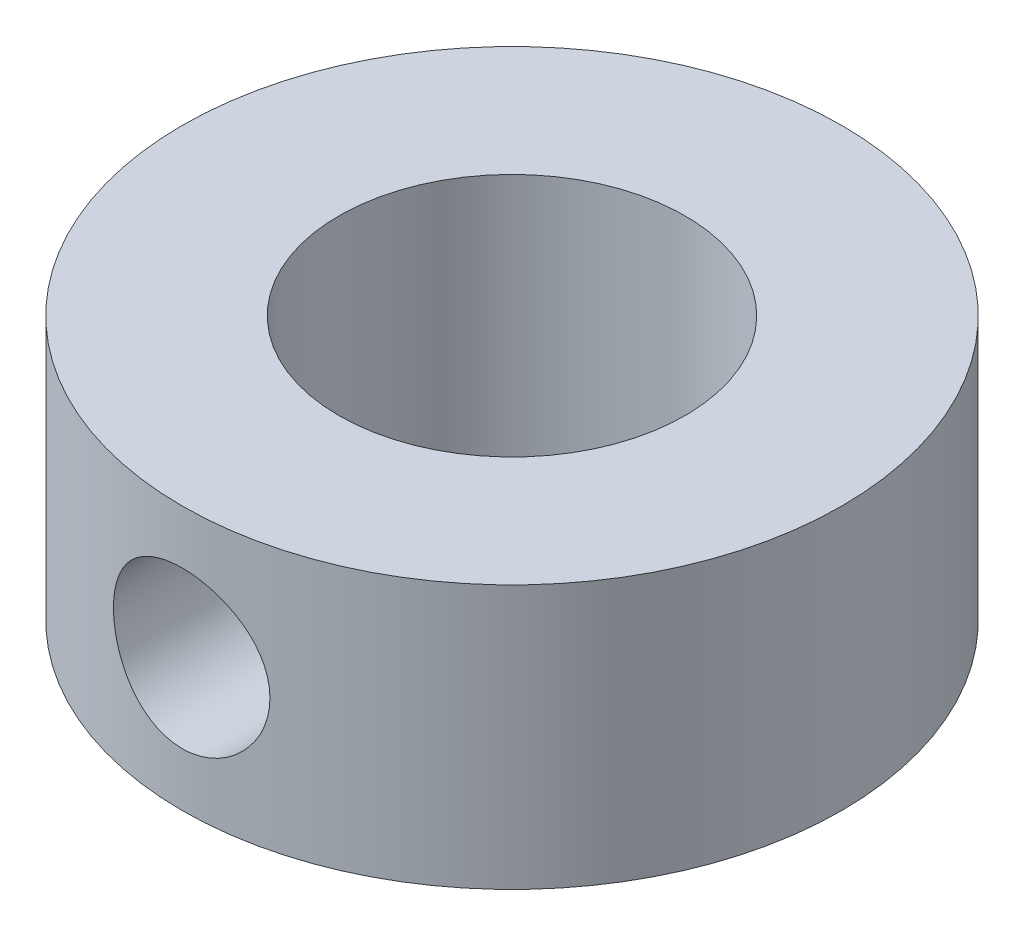
SolidWorks part; units mm, degrees
material "Cast Alloy Steel"
ref_plane "Front Plane" through (0, 0, 0) normal (0, 0, 1) x (1, 0, 0)
ref_plane "Top Plane" through (0, 0, 0) normal (0, 1, 0) x (1, 0, 0)
ref_plane "Right Plane" through (0, 0, 0) normal (1, 0, 0) x (0, 0, -1)
sketch "Sketch1" plane through (0, 0, 0) normal (0, 1, 0) x (1, 0, 0)
  circle A0 centre (0, 0) radius 2.5
  circle A1 centre (0, 0) radius 4.7625
  dimension "D1" = 9.525
  dimension "D2" = 5
extrude "Boss-Extrude1" add sketch "Sketch1" along normal blind 3.81
hole_wizard "#4-40 Tapped Hole1" positions "Sketch4" profile "Sketch3" tap size "#4-40" standard "ANSI Inch"
sketch "Sketch4" plane through (0, 0, 0) normal (0, 0, 1) x (1, 0, 0)
  line L0 (4.7625, 3.81) -> (-4.7625, 3.81) construction
  line L1 (-4.7625, 0) -> (4.7625, 0) construction
  line L2 (4.7625, 3.81) -> (-4.7625, 3.81) construction
  line L3 (-4.7625, 0) -> (4.7625, 0) construction
  line L4 (0, 0) -> (0, 3.81) construction
  point P0 (0, 1.905)
sketch "Sketch3" plane through (0, 1.905, 0) normal (1, 0, 0) x (0, 1, 0)
  line L0 (0, 0) -> (0, 4.7625)
  line L1 (0, 4.7625) -> (1.1303, 4.7625)
  line L2 (1.1303, 4.7625) -> (1.1303, 0)
  line L5 (1.1303, 0) -> (0, 0)
  line L11 (0, -6.35) -> (0, 107.95) construction
  dimension "Thru Tap Drill Dia." = 2.2606
  dimension "Thru Tap Drill Depth" = 4.7625
cosmetic thread "Hole Thread1" parameters "D2"=2.8448
